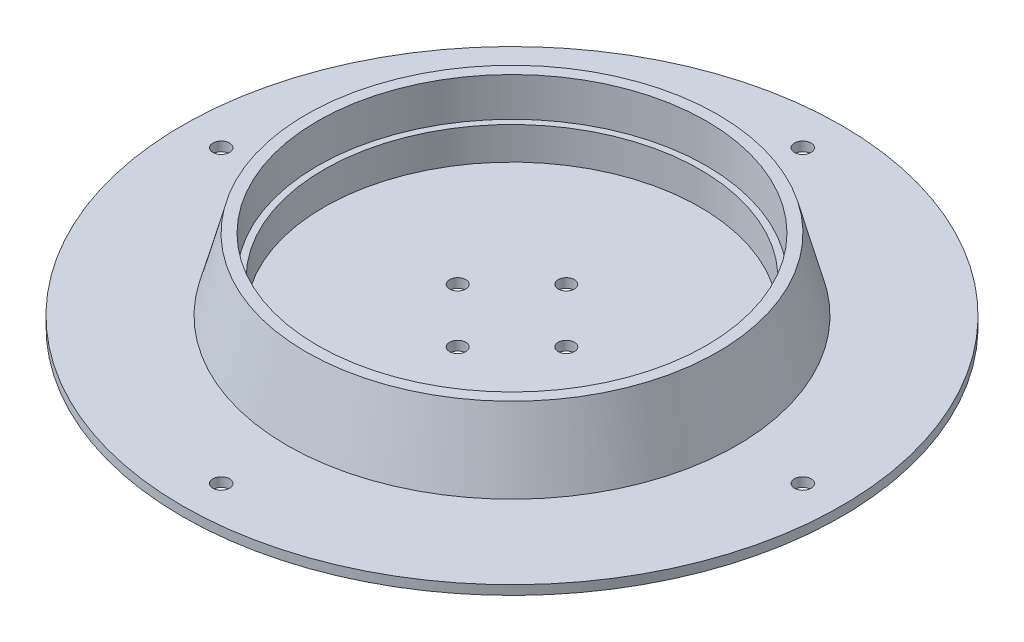
SolidWorks part; units mm, degrees
ref_plane "Front Plane" through (0, 0, 0) normal (0, 0, 1) x (1, 0, 0)
ref_plane "Top Plane" through (0, 0, 0) normal (0, 1, 0) x (1, 0, 0)
ref_plane "Right Plane" through (0, 0, 0) normal (1, 0, 0) x (0, 0, -1)
sketch "Sketch1" plane through (0, 0, 0) normal (0, 1, 0) x (1, 0, 0)
  circle A0 centre (0, 0) radius 85
  circle A1 centre (-75, 0) radius 2.1325
  circle A2 centre (0, 75) radius 2.1325
  circle A3 centre (75, 0) radius 2.1325
  circle A4 centre (0, -75) radius 2.1325
  circle A9 centre (-14, 0) radius 2.1
  circle A10 centre (0, 14) radius 2.1
  circle A11 centre (14, 0) radius 2.1
  circle A12 centre (0, -14) radius 2.1
  point P14 (0, 0)
  point P23 (0, 0)
  point P32 (0, 0)
  dimension "D1" = 75
  dimension "D3" = 170
  dimension "D5" = 14
  dimension "D4" = 4.2649
  dimension "D7" = 4.2
  dimension "D2" = 4
  dimension "D6" = 4
extrude "Boss-Extrude1" add sketch "Sketch1" along normal blind 2.4
sketch "Sketch2" plane through (0, 2.4, 0) normal (0, 1, 0) x (1, 0, 0)
  circle A0 centre (0, 0) radius 58
  dimension "D1" = 116
extrude "Boss-Extrude2" add sketch "Sketch2" along normal blind 18.4 draft 15
sketch "Sketch3" plane through (0, 20.8, 0) normal (0, 1, 0) x (1, 0, 0)
  circle A0 centre (0, 0) radius 50.15
  dimension "D1" = 100.3
extrude "Cut-Extrude1" cut sketch "Sketch3" against normal blind 10
sketch "Sketch4" plane through (0, 10.8, 0) normal (0, 1, 0) x (1, 0, 0)
  circle A0 centre (0, 0) radius 48.5
extrude "Cut-Extrude2" cut sketch "Sketch4" against normal blind 8.4
